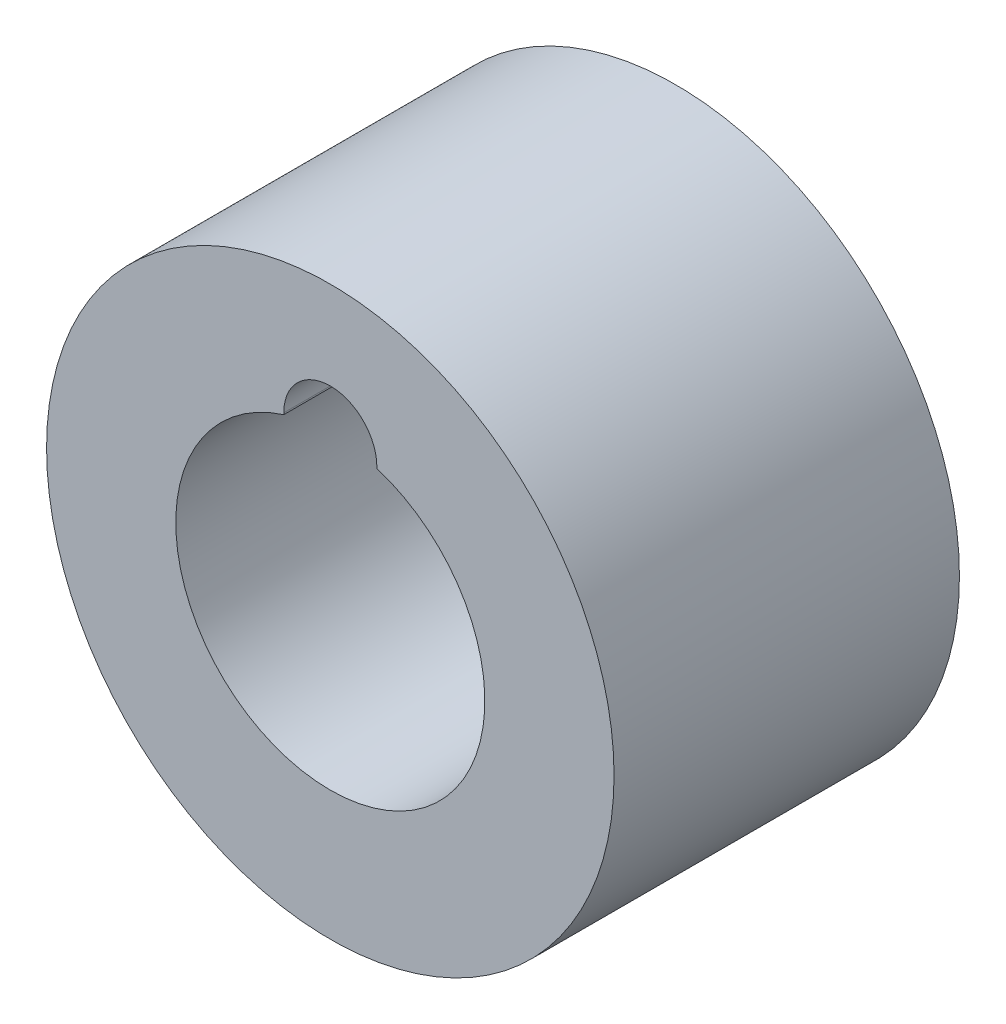
SolidWorks part; units mm, degrees
ref_plane "Alzado" through (0, 0, 0) normal (0, 0, 1) x (1, 0, 0)
ref_plane "Planta" through (0, 0, 0) normal (0, 1, 0) x (1, 0, 0)
ref_plane "Vista lateral" through (0, 0, 0) normal (1, 0, 0) x (0, 0, -1)
sketch "Croquis1" plane through (0, 0, 0) normal (0, 0, 1) x (1, 0, 0)
  circle A0 centre (0, 0) radius 4.15
  circle A1 centre (0, 0) radius 7.62
  dimension "D1" = 8.3
  dimension "D2" = 15.24
extrude "Saliente-Extruir1" add sketch "Croquis1" along normal blind 9.275
sketch "Croquis2" plane through (0, 0, 9.275) normal (0, 0, 1) x (1, 0, 0)
  line L0 (0, 0) -> (0, 4) construction
  line L1 (-1.25, 0) -> (-1.25, 4)
  line L2 (1.25, 0) -> (1.25, 4)
  circle A0 centre (0, 0) radius 4 construction
  arc A1 (-1.25, 0) -> (1.25, 0) centre (0, 0) ccw
  arc A2 (1.25, 4) -> (-1.25, 4) centre (0, 4) ccw
  point P4 (0, 2)
  dimension "D1" = 8
  dimension "D2" = 1.25
extrude "Cortar-Extruir1" cut sketch "Croquis2" against normal through all
